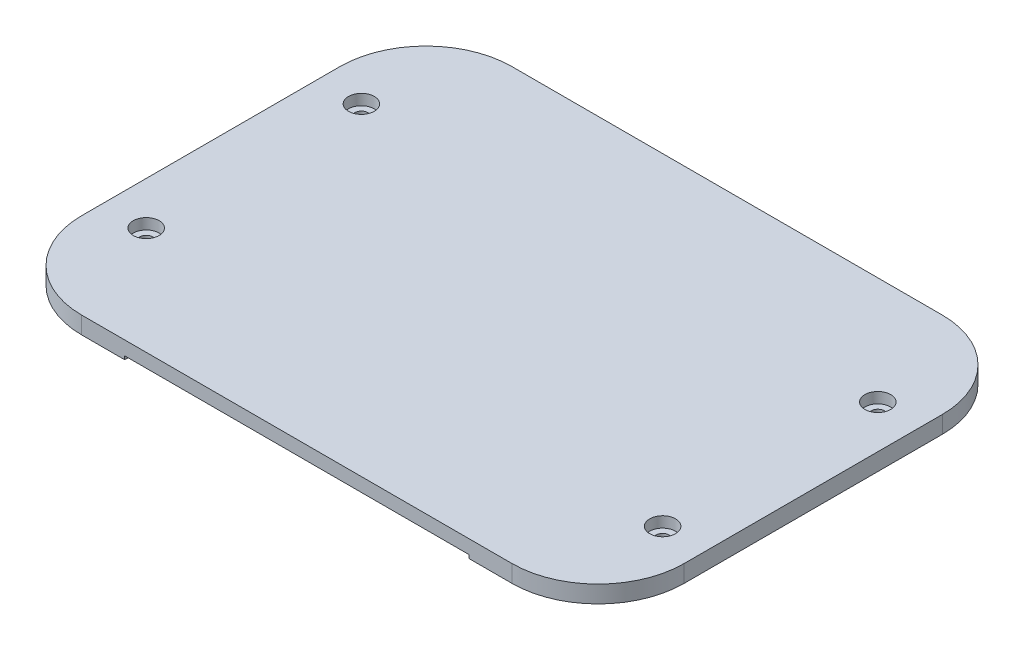
SolidWorks part; units mm, degrees
ref_plane "前视基准面" through (0, 0, 0) normal (0, 0, 1) x (1, 0, 0)
ref_plane "上视基准面" through (0, 0, 0) normal (0, 1, 0) x (1, 0, 0)
ref_plane "右视基准面" through (0, 0, 0) normal (1, 0, 0) x (0, 0, -1)
other "Configuration Table"
sketch "草图2" plane through (0, 0, 0) normal (0, 1, 0) x (1, 0, 0)
  line L1 (0, 0) -> (140, 0)
  line L2 (0, 0) -> (0, -100)
  line L3 (0, -100) -> (140, -100)
  line L4 (140, 0) -> (140, -100)
  line L6 (130, -50) -> (130, -25)
  line L8 (10, -50) -> (10, -75)
  line L9 (10, -50) -> (10, -25)
  line L10 (130, -50) -> (130, -75)
  circle A0 centre (10, -25) radius 1.5
  circle A1 centre (10, -75) radius 1.5
  circle A2 centre (130, -75) radius 1.5
  circle A3 centre (130, -25) radius 1.5
extrude "凸台-拉伸1" add sketch "草图2" along normal blind 5
fillet "圆角1" radius 20 4 edges at (0, 2.5, 100) (140, 2.5, 0) (140, 2.5, 100) (0, 2.5, 0)
sketch "草图3" plane through (0, 5, 0) normal (0, 1, 0) x (1, 0, 0)
  circle A0 centre (10, -25) radius 3
  circle A1 centre (10, -75) radius 3
  circle A2 centre (130, -25) radius 3
  circle A3 centre (130, -75) radius 3
extrude "切除-拉伸1" cut sketch "草图3" against normal blind 3
sketch "草图4" plane through (0, 0, 0) normal (0, -1, 0) x (1, 0, 0)
  line L0 (30, 100) -> (110, 100)
  line L1 (30, 0) -> (110, 0)
  line L3 (30, 50) -> (30, 100)
  line L4 (20, 100) -> (120, 100) construction
  line L5 (30, 50) -> (30, 0)
  line L6 (20, 0) -> (120, 0) construction
  line L7 (110, 50) -> (110, 0)
  line L8 (110, 50) -> (110, 100)
extrude "切除-拉伸2" cut sketch "草图4" against normal blind 0.9
sketch "草图5" plane through (0, 0, 0) normal (0, -1, 0) x (1, 0, 0)
  line L0 (30, 100) -> (110, 0)
  line L1 (70, 50) -> (120, 50)
  line L2 (70, 50) -> (20, 50)
  line L3 (20, 50) -> (20, 90)
  line L4 (20, 50) -> (20, 10)
  line L5 (120, 50) -> (120, 10)
  line L6 (120, 50) -> (120, 90)
  circle A0 centre (20, 90) radius 2.5
  circle A1 centre (120, 90) radius 2.5
  circle A2 centre (120, 10) radius 2.5
  circle A3 centre (20, 10) radius 2.5
extrude "切除-拉伸3" cut sketch "草图5" against normal blind 4
sketch "草图6" plane through (0, 5, 0) normal (0, 1, 0) x (1, 0, 0)
  line L1 (0, -102.0329) -> (157.6518, -102.0329)
  line L2 (0, -102.0329) -> (0, 0)
  line L3 (0, 0) -> (157.6518, 0)
  line L4 (157.6518, -102.0329) -> (157.6518, 0)
extrude "切除-拉伸4" cut sketch "草图6" against normal blind 1
sketch "草图7" plane through (0, 4, 0) normal (0, 1, 0) x (1, 0, 0)
  circle A0 centre (20, -10) radius 2.5
  circle A1 centre (120, -10) radius 2.5
  circle A2 centre (120, -90) radius 2.5
  circle A3 centre (20, -90) radius 2.5
extrude "凸台-拉伸2" add sketch "草图7" against normal blind 1
sketch "草图8" plane through (0, 2, 0) normal (0, 1, 0) x (1, 0, 0)
  circle A0 centre (10, -25) radius 3
  circle A1 centre (10, -75) radius 3
  circle A2 centre (130, -75) radius 3
  circle A3 centre (130, -25) radius 3
extrude "切除-拉伸5" cut sketch "草图8" against normal blind 0.5
sketch "草图9" plane through (0, 0, 0) normal (0, -1, 0) x (1, 0, 0)
  circle A1 centre (20, 90) radius 5.1
  circle A2 centre (120, 90) radius 5.1
  circle A3 centre (20, 10) radius 4.8851
  circle A4 centre (120, 10) radius 5.1
extrude "切除-拉伸6" cut sketch "草图9" against normal blind 3
sketch "草图10" plane through (0, 0.9, 0) normal (0, -1, 0) x (1, 0, 0)
  line L1 (30, 100) -> (110, 100)
  line L2 (30, 100) -> (30, 0)
  line L3 (30, 0) -> (110, 0)
  line L4 (110, 100) -> (110, 0)
extrude "凸台-拉伸3" add sketch "草图10" along normal blind 0.1
